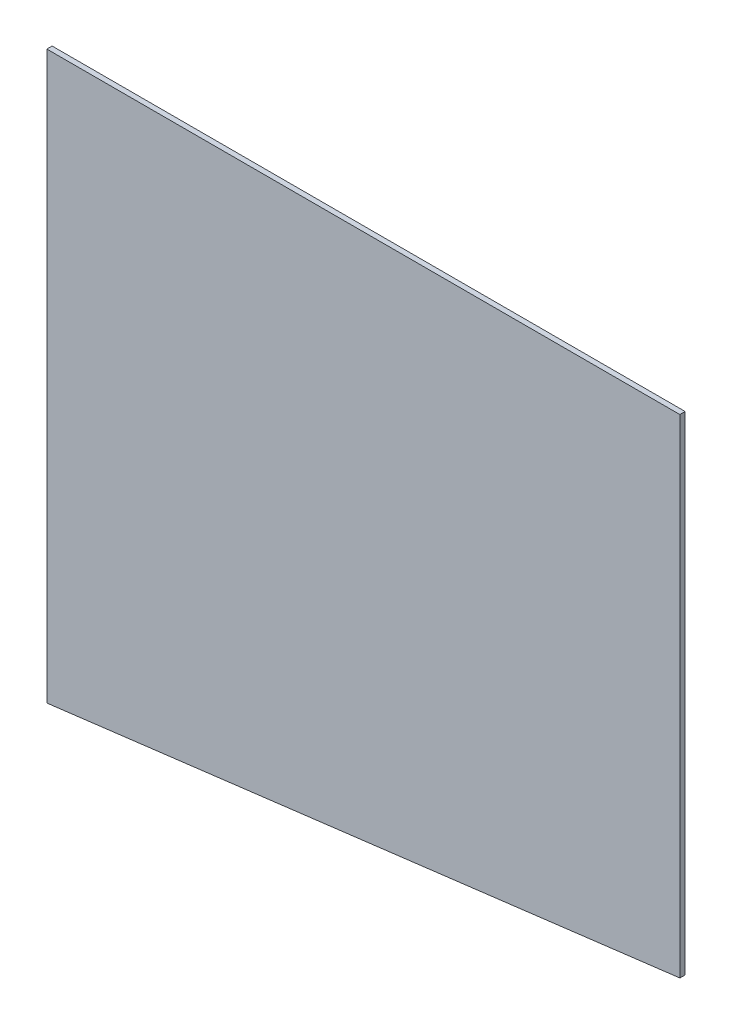
SolidWorks part; units mm, degrees
ref_plane "Front Plane" through (0, 0, 0) normal (0, 0, 1) x (1, 0, 0)
ref_plane "Top Plane" through (0, 0, 0) normal (0, 1, 0) x (1, 0, 0)
ref_plane "Right Plane" through (0, 0, 0) normal (1, 0, 0) x (0, 0, -1)
sketch "Sketch1" plane through (0, 0, 0) normal (0, 0, 1) x (1, 0, 0)
  line L4 (299.49, -216.4294) -> (59.49, -216.4294)
  line L5 (59.49, -216.4294) -> (59.49, -431.1554)
  line L7 (299.49, -401.4294) -> (299.49, -216.4294)
  line L8 (299.49, -401.4294) -> (59.49, -431.1554)
  point P0 (0, 0)
  dimension "D1" = 240
  dimension "D2" = 185
extrude "Boss-Extrude1" add sketch "Sketch1" along normal blind 2
